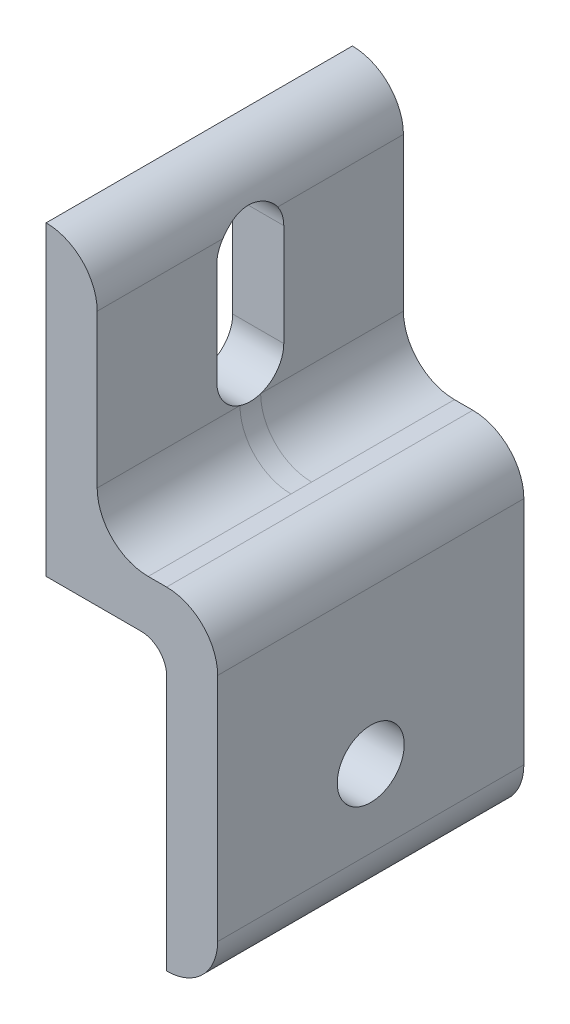
SolidWorks part; units mm, degrees
ref_plane "Front Plane" through (0, 0, 0) normal (0, 0, 1) x (1, 0, 0)
ref_plane "Top Plane" through (0, 0, 0) normal (0, 1, 0) x (1, 0, 0)
ref_plane "Right Plane" through (0, 0, 0) normal (1, 0, 0) x (0, 0, -1)
ref_plane "Plane1" through (0, 0, 19.05) normal (0, 0, 1) x (1, 0, 0)
sketch "Sketch1" plane through (0, 0, 19.05) normal (0, 0, 1) x (1, 0, 0)
  line L0 (0, 38.1) -> (0, 0)
  line L1 (0, 0) -> (14.986, 0)
  line L2 (14.986, 0) -> (14.986, -35.0266)
  line L3 (21.336, -28.6766) -> (21.336, 6.35)
  line L4 (21.336, 6.35) -> (6.35, 6.35)
  line L5 (6.35, 6.35) -> (6.35, 31.75)
  arc A0 (14.986, -35.0266) -> (21.336, -28.6766) centre (14.986, -28.6766) ccw
  arc A1 (6.35, 31.75) -> (0, 38.1) centre (0, 31.75) ccw
extrude "Boss-Extrude1" add sketch "Sketch1" against normal blind 38.1
sketch "Sketch2" plane through (0, 0, 0) normal (-1, 0, 0) x (0, 0, 1)
  line L0 (-4.1656, 29.3624) -> (-4.1656, 16.6624)
  line L1 (4.1656, 16.6624) -> (4.1656, 29.3624)
  arc A0 (4.1656, 29.3624) -> (-4.1656, 29.3624) centre (0, 29.3624) ccw
  arc A1 (-4.1656, 16.6624) -> (4.1656, 16.6624) centre (0, 16.6624) ccw
extrude "Cut-Extrude1" cut sketch "Sketch2" against normal through all
hole_wizard "5/16 Clearance Hole1" positions "Sketch4" profile "Sketch3" hole size "5/16" standard "ANSI Inch"
sketch "Sketch4" plane through (14.986, 0, 0) normal (-1, 0, 0) x (0, 0, 1)
  point P0 (0, -19.05)
sketch "Sketch3" plane through (14.986, -19.05, 0) normal (0, 1, 0) x (0, 0, 1)
  line L0 (0, 0) -> (0, 6.35)
  line L1 (0, 6.35) -> (4.1656, 6.35)
  line L2 (4.1656, 6.35) -> (4.1656, 0)
  line L5 (4.1656, 0) -> (0, 0)
  line L11 (0, -6.35) -> (0, 107.95) construction
  dimension "Thru Hole Dia." = 8.3312
  dimension "Thru Hole Depth" = 6.35
fillet "Fillet1" radius 3.175 1 edges at (14.986, 0, 0)
fillet "Fillet2" radius 6.35 2 edges at (6.35, 6.35, 0) (21.336, 6.35, 0)
